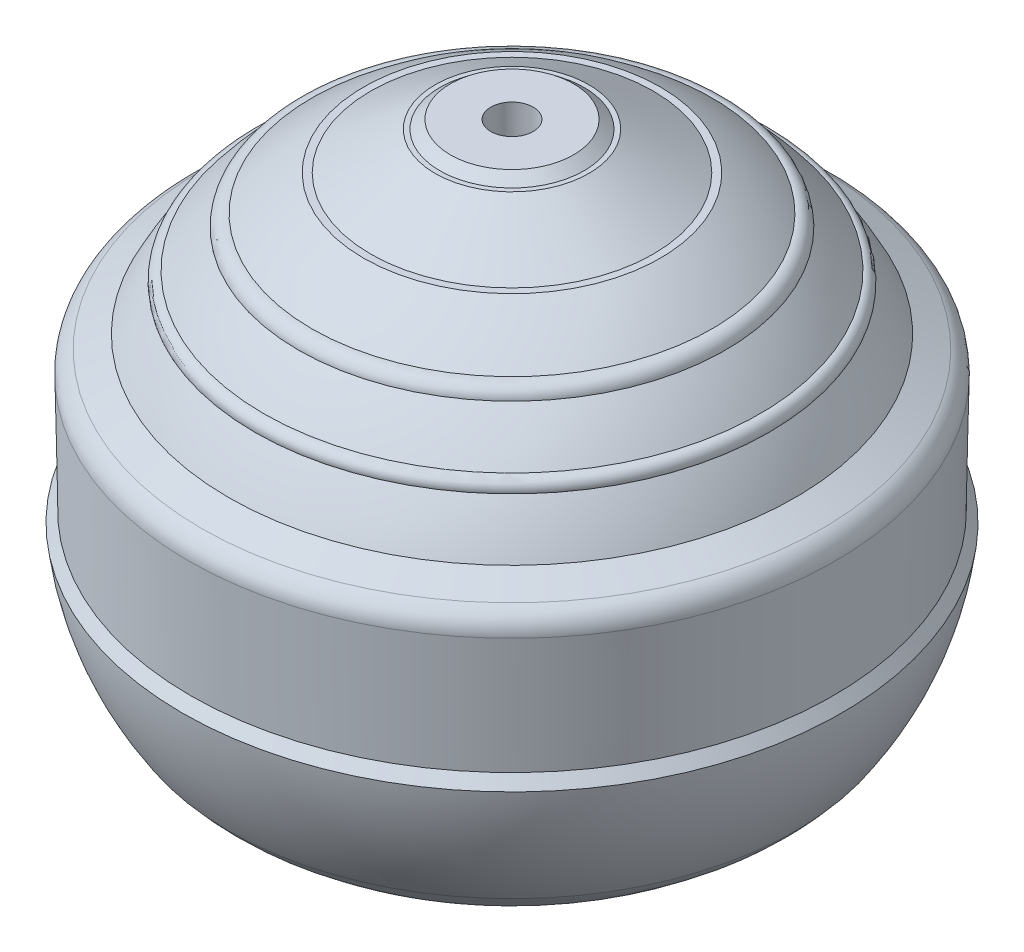
SolidWorks part; units mm, degrees
material "3.3549 (EN-AW 5182)"
ref_plane "Ön Düzlem" through (0, 0, 0) normal (0, 0, 1) x (1, 0, 0)
ref_plane "Üst Düzlem" through (0, 0, 0) normal (0, 1, 0) x (1, 0, 0)
ref_plane "Sağ Düzlem" through (0, 0, 0) normal (1, 0, 0) x (0, 0, -1)
sketch "Çizim1" plane through (0, 0, 0) normal (0, 0, 1) x (1, 0, 0)
  line L0 (0, 0) -> (0, -2.0338)
  line L1 (9.2555, -21.6377) -> (10.2575, -21.6377)
  line L2 (14, -14.8465) -> (13.65, -14.3817)
  line L3 (13.65, -14.3817) -> (13.7388, -9.38)
  line L4 (13.182, -8.4658) -> (12.0358, -7.8994)
  line L5 (6.302, -1.9598) -> (6.002, -1.9598)
  line L6 (6.002, -1.9598) -> (3.2662, -0.3598)
  line L7 (3.2662, -0.3598) -> (3.0662, -0.3598)
  line L8 (3.0662, -0.3598) -> (2.6164, 0)
  line L9 (0, 0) -> (0.9, 0)
  line L10 (2.6164, 0) -> (0.9, 0)
  line L11 (0, -2.0338) -> (0.9, -2.0338)
  arc A0 (10.2575, -21.6377) -> (12.0358, -20.1628) centre (7.3054, -16.2689) ccw
  arc A1 (13.7388, -9.38) -> (13.182, -8.4658) centre (12.7389, -9.3623) ccw
  arc A2 (12.0358, -7.8994) -> (10.9196, -6.0598) centre (-0.4558, -14.2208) ccw
  arc A3 (10.9196, -6.0598) -> (10.5436, -5.5598) centre (10.5268, -5.9638) ccw
  arc A4 (10.5436, -5.5598) -> (9.0685, -3.9598) centre (-0.4558, -14.2208) ccw
  arc A5 (9.0685, -3.9598) -> (8.4997, -3.4598) centre (8.5313, -3.9974) ccw
  arc A6 (8.4997, -3.4598) -> (6.302, -1.9598) centre (-0.4558, -14.2208) ccw
  arc A7 (9.2555, -21.6377) -> (0.9, -2.0338) centre (0, -14) ccw
  arc A8 (12.0358, -20.1628) -> (14, -14.8465) centre (2.08, -13.4634) ccw
revolve "Döndür1" add sketch "Çizim1" angle 360 about L0
sketch "Çizim2" plane through (0, 0, 0) normal (0, 1, 0) x (1, 0, 0)
  circle A0 centre (0, 0) radius 0.9
extrude "Kes-Ekstrüzyon1" cut sketch "Çizim2" against normal blind 10
